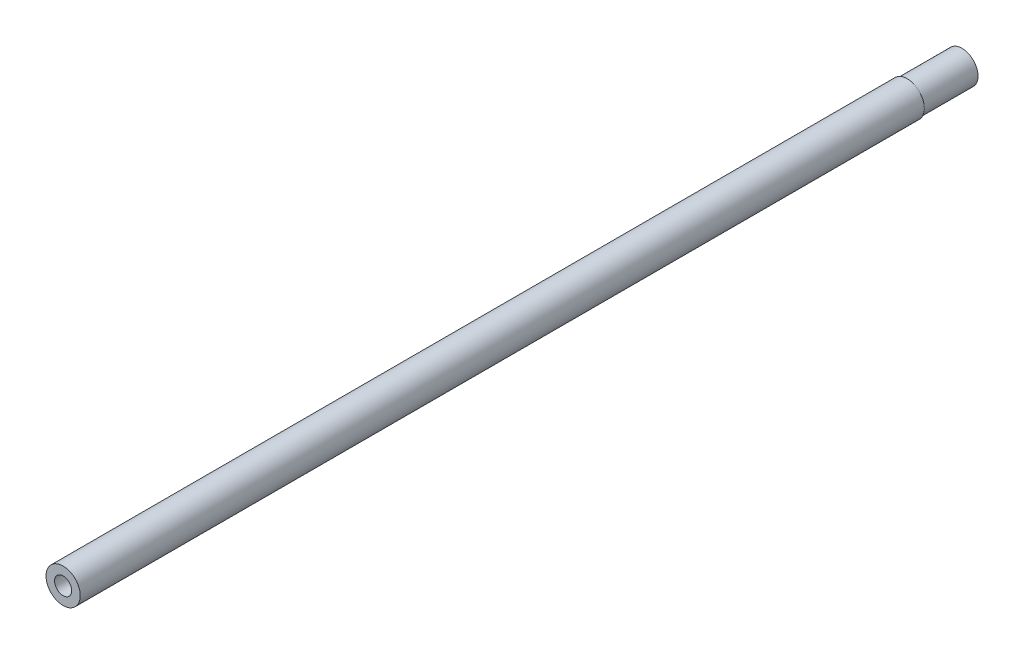
SolidWorks part; units mm, degrees
material "45"
ref_plane "前视基准面" through (0, 0, 0) normal (0, 0, 1) x (1, 0, 0)
ref_plane "上视基准面" through (0, 0, 0) normal (0, 1, 0) x (1, 0, 0)
ref_plane "右视基准面" through (0, 0, 0) normal (1, 0, 0) x (0, 0, -1)
sketch "草图1" plane through (0, 0, 0) normal (0, 0, 1) x (1, 0, 0)
  circle A0 centre (0, 0) radius 40
  circle A1 centre (0, 0) radius 20
  dimension "D1" = 80
  dimension "D2" = 40
extrude "凸台-拉伸1" add sketch "草图1" along normal blind 2100
sketch "草图2" plane through (0, 0, 0) normal (0, 0, -1) x (-1, 0, 0)
  circle A0 centre (0, 0) radius 40
  circle A1 centre (0, 0) radius 37.5
  dimension "D1" = 75
  dimension "D2" = 80
extrude "切除-拉伸1" cut sketch "草图2" against normal blind 128
